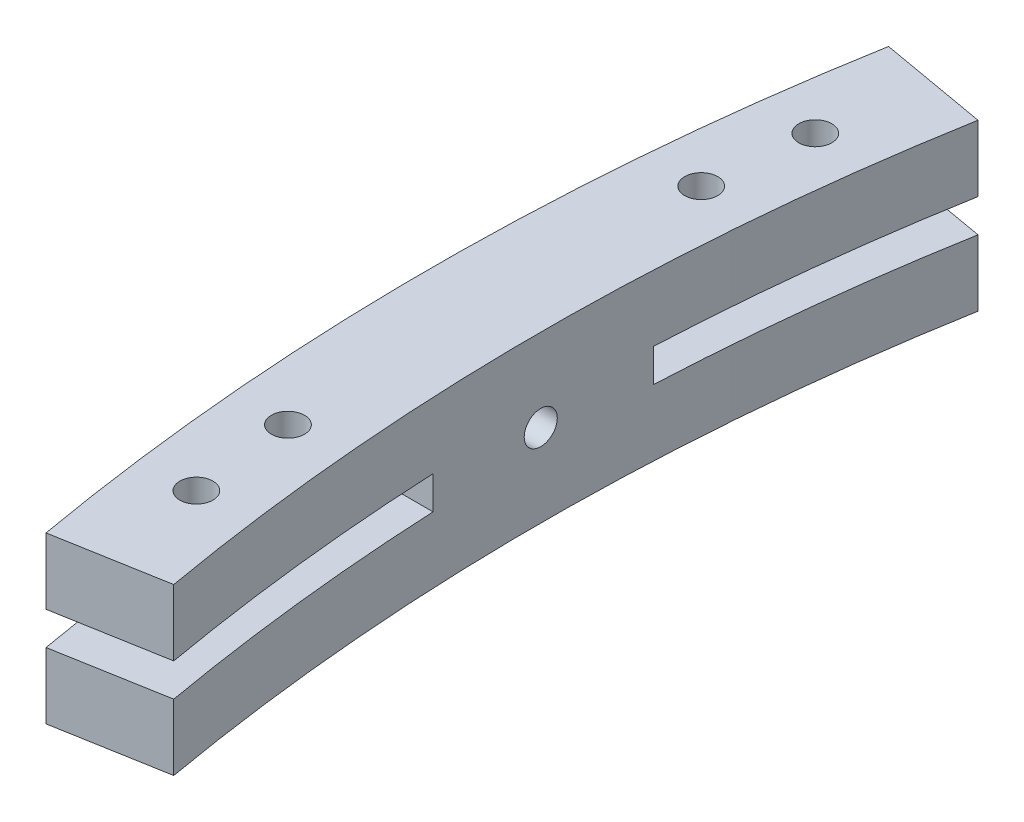
SolidWorks part; units mm, degrees
ref_plane "Front Plane" through (0, 0, 0) normal (0, 0, 1) x (1, 0, 0)
ref_plane "Top Plane" through (0, 0, 0) normal (0, 1, 0) x (1, 0, 0)
ref_plane "Right Plane" through (0, 0, 0) normal (1, 0, 0) x (0, 0, -1)
sketch "Sketch1" plane through (0, 0, 0) normal (0, 0, 1) x (1, 0, 0)
  line L0 (190, 0) -> (-190, 0) construction
  line L1 (0, 190) -> (0, -190) construction
  line L2 (0, 0) -> (-187.1135, 32.9932) construction
  line L3 (0, 0) -> (-187.1135, -32.9932) construction
  line L4 (-187.1135, 32.9932) -> (-196.9616, 34.7296)
  line L5 (-187.1135, -32.9932) -> (-196.9616, -34.7296)
  arc A0 (-187.1135, 32.9932) -> (-187.1135, -32.9932) centre (0, 0) ccw
  arc A1 (-196.9616, 34.7296) -> (-196.9616, -34.7296) centre (0, 0) ccw
  circle A3 centre (0, 0) radius 190 construction
  dimension "D1" = 380
  dimension "D2" = 10
  dimension "D3" = 20
sketch "Sketch9" plane through (0, 0, 0) normal (0, 1, 0) x (1, 0, 0)
  line L0 (0, 0) -> (-196.9616, 34.7296)
  line L1 (-200, 0) -> (200, 0) construction
  line L2 (0, 0) -> (-196.9616, -34.7296)
  circle A0 centre (0, 0) radius 195 construction
  circle A1 centre (0, 0) radius 195 construction
  circle A8 centre (0, 0) radius 200 construction
  circle A9 centre (0, 0) radius 190 construction
  circle A10 centre (0, 0) radius 200
  circle A11 centre (0, 0) radius 190
  dimension "D1" = 20
extrude "base" [suppressed] add sketch "Sketch9" along normal mid plane 15 contours A11 L0 A10 L2
sketch "Sketch11" [suppressed] plane through (0, 0, 0) normal (0, 1, 0) x (1, 0, 0)
  line L8 (-189.7367, -10) -> (-199.7498, -10) construction
  line L9 (-187.1135, -32.9932) -> (-196.9616, -34.7296) construction
  line L10 (-189.7367, 10) -> (-199.7498, 10) construction
  line L11 (-187.1135, 32.9932) -> (-196.9616, 34.7296) construction
  line L12 (-189.7367, -10) -> (-199.7498, -10)
  line L13 (-187.1135, -32.9932) -> (-196.9616, -34.7296)
  line L14 (-189.7367, 10) -> (-199.7498, 10)
  line L15 (-187.1135, 32.9932) -> (-196.9616, 34.7296)
  circle A14 centre (0, 0) radius 200 construction
  circle A15 centre (0, 0) radius 190 construction
  arc A16 (-196.9616, 34.7296) -> (-199.7498, 10) centre (0, 0) ccw
  arc A17 (-187.1135, 32.9932) -> (-189.7367, 10) centre (0, 0) ccw
  arc A18 (-199.7498, -10) -> (-196.9616, -34.7296) centre (0, 0) ccw
  arc A19 (-189.7367, -10) -> (-187.1135, -32.9932) centre (0, 0) ccw
extrude "Cut-Extrude8" [suppressed] cut sketch "Sketch11" along normal up to surface and the other way up to surface
sketch "Sketch12" plane through (0, 0, 0) normal (0, 1, 0) x (1, 0, 0)
  line L0 (-200, 0) -> (200, 0) construction
  line L1 (-200, 0) -> (200, 0) construction
  circle A0 centre (0, 0) radius 195 construction
  circle A1 centre (0, 0) radius 195 construction
  circle A2 centre (-193.3908, 25) radius 1.5
  circle A3 centre (-194.4222, 15) radius 1.5
  circle A4 centre (-194.4222, -15) radius 1.5
  circle A5 centre (-193.3908, -25) radius 1.5
  dimension "D1" = 3
  dimension "D2" = 30
  dimension "D3" = 50
extrude "Cut-Extrude9" [suppressed] cut sketch "Sketch12" against normal through all both and the other way through all
sketch "Sketch13" plane through (0, 0, 0) normal (0, 1, 0) x (1, 0, 0)
  line L2 (0, 0) -> (-216.6577, 38.2026)
  line L4 (-215, 0) -> (215, 0) construction
  line L5 (-215, 0) -> (215, 0) construction
  line L6 (0, 0) -> (-216.6577, -38.2026)
  line L7 (-209.7618, -10) -> (-219.7726, -10) construction
  line L8 (-209.7618, 10) -> (-219.7726, 10) construction
  line L9 (-209.7618, -10) -> (-219.7726, -10)
  line L10 (-209.7618, 10) -> (-219.7726, 10)
  circle A5 centre (0, 0) radius 215 construction
  circle A6 centre (0, 0) radius 220 construction
  circle A7 centre (0, 0) radius 210 construction
  circle A8 centre (0, 0) radius 220
  circle A9 centre (0, 0) radius 210
  dimension "D1" = 20
extrude "base2" add sketch "Sketch13" along normal mid plane 15 contours A9 L2 A8 L10 | A9 L10 A8 L9 | A9 L9 A8 L6
sketch "Sketch14" plane through (0, 0, 0) normal (0, 1, 0) x (1, 0, 0)
  line L0 (-209.7618, -10) -> (-219.7726, -10) construction
  line L1 (-209.7618, 10) -> (-219.7726, 10) construction
  line L2 (-209.7618, -10) -> (-219.7726, -10)
  line L3 (-209.7618, 10) -> (-219.7726, 10)
  line L4 (0, 0) -> (-216.6577, 38.2026) construction
  line L5 (0, 0) -> (-216.6577, -38.2026) construction
  line L6 (-206.8096, 36.4661) -> (-216.6577, 38.2026)
  line L7 (-206.8096, -36.4661) -> (-216.6577, -38.2026)
  arc A0 (-219.7726, -10) -> (-216.6577, -38.2026) centre (0, 0) ccw
  arc A1 (-209.7618, -10) -> (-206.8096, -36.4661) centre (0, 0) ccw
  circle A4 centre (0, 0) radius 220 construction
  circle A5 centre (0, 0) radius 210 construction
  arc A6 (-216.6577, 38.2026) -> (-219.7726, 10) centre (0, 0) ccw
  arc A7 (-206.8096, 36.4661) -> (-209.7618, 10) centre (0, 0) ccw
extrude "mount2" cut sketch "Sketch14" along normal up to surface and the other way up to surface
sketch "Sketch16" plane through (0, 0, 0) normal (0, 1, 0) x (1, 0, 0)
  line L0 (-214.1819, 18.7385) -> (0, 0) construction
  line L1 (0, 0) -> (-213.1606, 28.0631) construction
  line L3 (0, 0) -> (-215, 0) construction
  line L4 (-214.1819, -18.7385) -> (0, 0) construction
  line L5 (0, 0) -> (-213.1606, -28.0631) construction
  circle A0 centre (0, 0) radius 215 construction
  circle A1 centre (0, 0) radius 215 construction
  circle A2 centre (-213.1606, 28.0631) radius 1.5
  circle A3 centre (-214.1819, 18.7385) radius 1.5
  circle A4 centre (-214.1819, -18.7385) radius 1.5
  circle A5 centre (-213.1606, -28.0631) radius 1.5
  dimension "D1" = 3
  dimension "D2" = 10
  dimension "D3" = 15
extrude "mount hole2" cut sketch "Sketch16" against normal through all both and the other way through all
ref_plane "shaft" through (-215, 0, 0) normal (1, 0, 0) x (0, 0, -1)
sketch "Sketch17" plane through (-215, 0, 0) normal (1, 0, 0) x (0, 0, -1)
  circle A0 centre (0, 0) radius 1.5
  dimension "D1" = 3
extrude "shaft hole" cut sketch "Sketch17" along normal through all
sketch "Sketch18" plane through (0, 0, 0) normal (0, 1, 0) x (1, 0, 0)
  line L6 (-213.75, 3) -> (-216.25, 3) construction
  line L7 (-213.75, 3) -> (-213.75, -3) construction
  line L8 (-213.75, -3) -> (-216.25, -3) construction
  line L9 (-216.25, 3) -> (-216.25, -3) construction
  line L10 (-213.75, 3) -> (-216.25, -3) construction
  line L11 (-213.75, -3) -> (-216.25, 3) construction
  line L12 (-216.25, 3) -> (-213.75, 3)
  line L13 (-216.25, 3) -> (-216.25, 0)
  line L14 (-216.25, 0) -> (-213.75, 0)
  line L15 (-213.75, 3) -> (-213.75, 0)
  point P0 (-215, 0)
  dimension "D1" = 6
  dimension "D2" = 2.5
revolve "Cut-Revolve1" cut sketch "Sketch18" angle 360 about L5
sketch "Sketch6" plane through (0, 0, 0) normal (0, 0, 1) x (1, 0, 0)
  line L1 (-208.5097, 7.5) -> (-171.4903, 7.5)
  line L2 (-208.5097, 7.5) -> (-208.5097, -7.5)
  line L3 (-208.5097, -7.5) -> (-171.4903, -7.5)
  line L4 (-171.4903, 7.5) -> (-171.4903, -7.5)
  line L5 (-208.5097, 7.5) -> (-171.4903, -7.5) construction
  line L6 (-208.5097, -7.5) -> (-171.4903, 7.5) construction
  arc A0 (-196.9616, 34.7296) -> (-196.9616, -34.7296) centre (0, 0) ccw construction
  arc A1 (-187.1135, 32.9932) -> (-187.1135, -32.9932) centre (0, 0) ccw construction
  arc A2 (-196.9616, 34.7296) -> (-196.9616, -34.7296) centre (0, 0) ccw
  arc A3 (-187.1135, 32.9932) -> (-187.1135, -32.9932) centre (0, 0) ccw
  point P0 (-190, 0)
  dimension "D1" = 15
ref_plane "Plane1" through (-190, 0, 0) normal (1, 0, 0) x (0, 0, -1)
sketch "Sketch4" plane through (-190, 0, 0) normal (1, 0, 0) x (0, 0, -1)
  circle A0 centre (0, 0) radius 3
  dimension "D1" = 6
sketch "Sketch7" plane through (-190, 0, 0) normal (1, 0, 0) x (0, 0, -1)
  circle A0 centre (0, 0) radius 1.5
  dimension "D1" = 3
